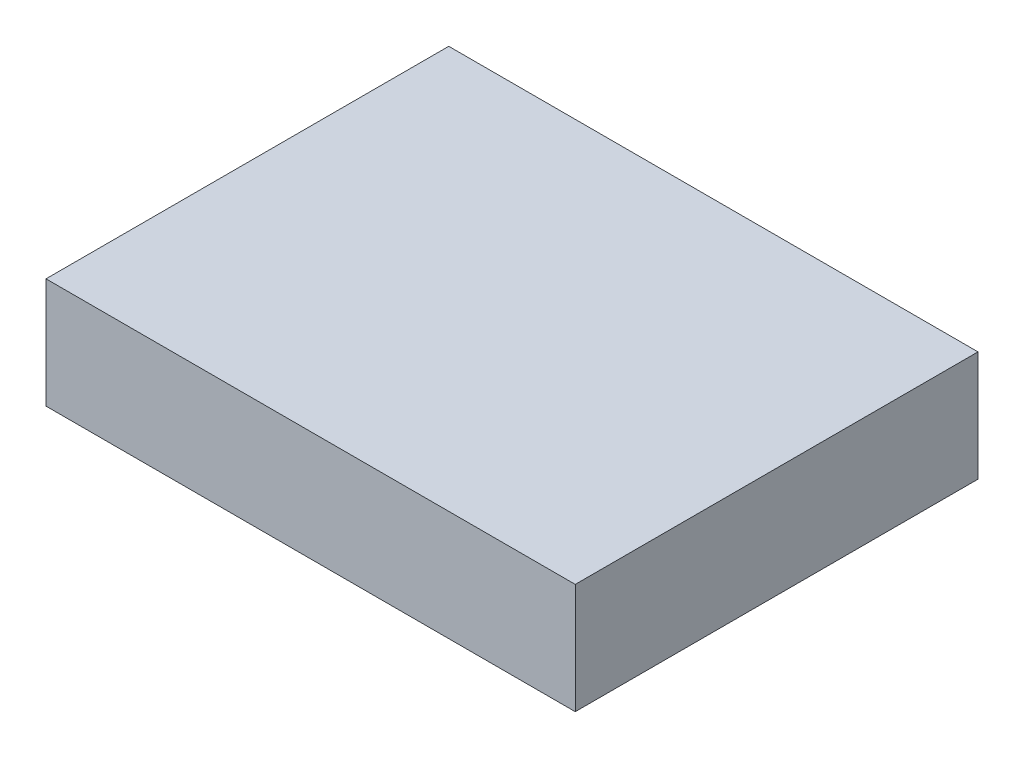
SolidWorks part; units mm, degrees
material "PPE"
ref_plane "Front Plane" through (0, 0, 0) normal (0, 0, 1) x (1, 0, 0)
ref_plane "Top Plane" through (0, 0, 0) normal (0, 1, 0) x (1, 0, 0)
ref_plane "Right Plane" through (0, 0, 0) normal (1, 0, 0) x (0, 0, -1)
sketch "Sketch1" plane through (0, 0, 0) normal (0, 1, 0) x (1, 0, 0)
  line L1 (-22.8, -17.35) -> (22.8, -17.35)
  line L2 (-22.8, -17.35) -> (-22.8, 17.35)
  line L3 (-22.8, 17.35) -> (22.8, 17.35)
  line L4 (22.8, -17.35) -> (22.8, 17.35)
  line L5 (-22.8, -17.35) -> (22.8, 17.35) construction
  line L6 (-22.8, 17.35) -> (22.8, -17.35) construction
  point P0 (0, 0)
  dimension "D1" = 34.7
  dimension "D2" = 45.6
extrude "Boss-Extrude1" add sketch "Sketch1" along normal blind 9.5
